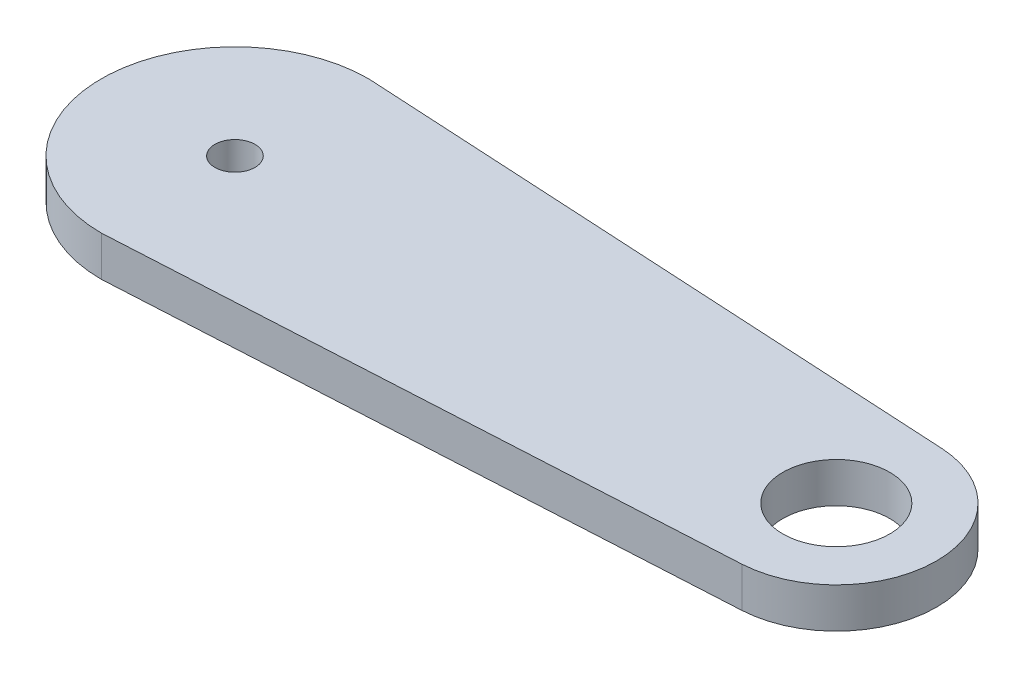
SolidWorks part; units mm, degrees
ref_plane "Front Plane" through (0, 0, 0) normal (0, 0, 1) x (1, 0, 0)
ref_plane "Top Plane" through (0, 0, 0) normal (0, 1, 0) x (1, 0, 0)
ref_plane "Right Plane" through (0, 0, 0) normal (1, 0, 0) x (0, 0, -1)
sketch "Sketch1" plane through (0, 0, 0) normal (0, 1, 0) x (1, 0, 0)
  line L0 (0, 10) -> (45.4141, 7.4886)
  line L1 (0, -10) -> (45.4141, -7.4886)
  circle A0 centre (0, 0) radius 10
  circle A1 centre (45, 0) radius 7.5
  dimension "D2" = 20
  dimension "D3" = 15
  dimension "D1" = 45
extrude "Boss-Extrude1" add sketch "Sketch1" along normal blind 3 contours L1 A0 L0 | A1 L0 A0 L1 | A1 L1
sketch "Sketch2" plane through (0, 3, 0) normal (0, 1, 0) x (1, 0, 0)
  circle A0 centre (0, 0) radius 1.5
  circle A1 centre (45, 0) radius 4
  dimension "D1" = 3
  dimension "D2" = 8
extrude "Cut-Extrude1" cut sketch "Sketch2" against normal up to next
